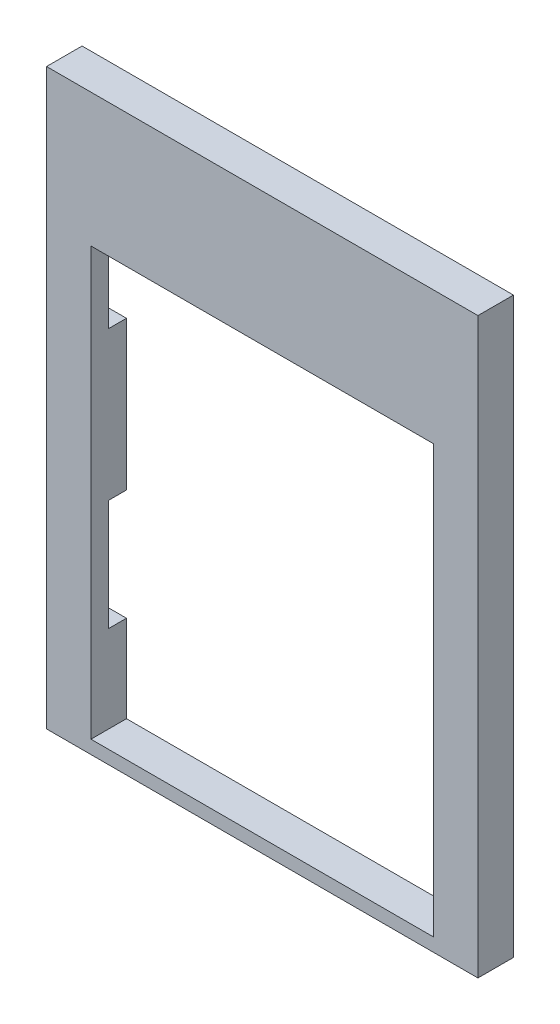
SolidWorks part; units mm, degrees
ref_plane "前视基准面" through (0, 0, 0) normal (0, 0, 1) x (1, 0, 0)
ref_plane "上视基准面" through (0, 0, 0) normal (0, 1, 0) x (1, 0, 0)
ref_plane "右视基准面" through (0, 0, 0) normal (1, 0, 0) x (0, 0, -1)
other "Configuration Table"
sketch "Model" plane through (0, 0, 0) normal (0, 0, 1) x (1, 0, 0)
  line L0 (114.6852, 14.7846) -> (114.6852, 10.0841)
  line L1 (114.6852, 10.0841) -> (113.1597, 10.0841)
  line L2 (113.1597, 10.0841) -> (113.1597, 13.3143)
  line L3 (113.1597, 13.3143) -> (106.4101, 13.3143)
  line L4 (106.4101, 13.3143) -> (106.4101, 10.0841)
  line L5 (106.4101, 10.0841) -> (105.5846, 10.0841)
  line L6 (105.5846, 10.0841) -> (105.5846, 7.2853)
  line L7 (105.5846, 7.2853) -> (106.4101, 7.2853)
  line L8 (106.4101, 7.2853) -> (106.4101, 1.0153)
  line L9 (106.4101, 1.0153) -> (108.1354, 1.0153)
  line L10 (108.1354, 1.0153) -> (108.1354, -0.185)
  line L11 (108.1354, -0.185) -> (111.4344, -0.185)
  line L12 (111.4344, -0.185) -> (111.4344, 1.0153)
  line L13 (111.4344, 1.0153) -> (113.1597, 1.0153)
  line L14 (113.1597, 1.0153) -> (113.1597, 5.4842)
  line L15 (113.1597, 5.4842) -> (114.6852, 5.4842)
  line L16 (114.6852, 5.4842) -> (114.6852, 0.7851)
  line L17 (114.6852, 0.7851) -> (128.6846, 0.7851)
  line L18 (128.6846, 0.7851) -> (128.6846, 5.4842)
  line L19 (128.6846, 5.4842) -> (130.2101, 5.4842)
  line L20 (130.2101, 5.4842) -> (130.2101, 1.0153)
  line L21 (130.2101, 1.0153) -> (131.9354, 1.0153)
  line L22 (131.9354, 1.0153) -> (131.9354, -0.185)
  line L23 (131.9354, -0.185) -> (135.2345, -0.185)
  line L24 (135.2345, -0.185) -> (135.2345, 1.0153)
  line L25 (135.2345, 1.0153) -> (136.9598, 1.0153)
  line L26 (136.9598, 1.0153) -> (136.9598, 7.2853)
  line L27 (136.9598, 7.2853) -> (137.7852, 7.2853)
  line L28 (137.7852, 7.2853) -> (137.7852, 10.0841)
  line L29 (137.7852, 10.0841) -> (136.9598, 10.0841)
  line L30 (136.9598, 10.0841) -> (136.9598, 13.3143)
  line L31 (136.9598, 13.3143) -> (130.2101, 13.3143)
  line L32 (130.2101, 13.3143) -> (130.2101, 10.0841)
  line L33 (130.2101, 10.0841) -> (128.6846, 10.0841)
  line L34 (128.6846, 10.0841) -> (128.6846, 14.7846)
  line L35 (128.6846, 14.7846) -> (114.6852, 14.7846)
  line L36 (143.2602, 14.7846) -> (157.2595, 14.7846)
  line L37 (157.2595, 14.7846) -> (157.2595, 0.7851)
  line L38 (157.2595, 0.7851) -> (143.2602, 0.7851)
  line L39 (143.2602, 0.7851) -> (143.2602, 14.7846)
  line L40 (168.8105, 33.4102) -> (168.8105, 32.5848)
  line L41 (168.8105, 32.5848) -> (162.5402, 32.5848)
  line L42 (162.5402, 32.5848) -> (162.5402, 30.8594)
  line L43 (162.5402, 30.8594) -> (161.3401, 30.8594)
  line L44 (161.3401, 30.8594) -> (161.3401, 27.5604)
  line L45 (161.3401, 27.5604) -> (162.5402, 27.5604)
  line L46 (162.5402, 27.5604) -> (162.5402, 25.8351)
  line L47 (162.5402, 25.8351) -> (167.0106, 25.8351)
  line L48 (167.0106, 25.8351) -> (167.0106, 24.3096)
  line L49 (167.0106, 24.3096) -> (162.3102, 24.3096)
  line L50 (162.3102, 24.3096) -> (162.3102, 10.3101)
  line L51 (162.3102, 10.3101) -> (167.0106, 10.3101)
  line L52 (167.0106, 10.3101) -> (167.0106, 8.7846)
  line L53 (167.0106, 8.7846) -> (162.5402, 8.7846)
  line L54 (162.5402, 8.7846) -> (162.5402, 7.0594)
  line L55 (162.5402, 7.0594) -> (161.3401, 7.0594)
  line L56 (161.3401, 7.0594) -> (161.3401, 3.7603)
  line L57 (161.3401, 3.7603) -> (162.5402, 3.7603)
  line L58 (162.5402, 3.7603) -> (162.5402, 2.035)
  line L59 (162.5402, 2.035) -> (168.8105, 2.035)
  line L60 (168.8105, 2.035) -> (168.8105, 1.2096)
  line L61 (168.8105, 1.2096) -> (171.6105, 1.2096)
  line L62 (171.6105, 1.2096) -> (171.6105, 2.035)
  line L63 (171.6105, 2.035) -> (174.8405, 2.035)
  line L64 (174.8405, 2.035) -> (174.8405, 8.7846)
  line L65 (174.8405, 8.7846) -> (171.6105, 8.7846)
  line L66 (171.6105, 8.7846) -> (171.6105, 10.3101)
  line L67 (171.6105, 10.3101) -> (176.3095, 10.3101)
  line L68 (176.3095, 10.3101) -> (176.3095, 24.3096)
  line L69 (176.3095, 24.3096) -> (171.6105, 24.3096)
  line L70 (171.6105, 24.3096) -> (171.6105, 25.8351)
  line L71 (171.6105, 25.8351) -> (174.8405, 25.8351)
  line L72 (174.8405, 25.8351) -> (174.8405, 32.5848)
  line L73 (174.8405, 32.5848) -> (171.6105, 32.5848)
  line L74 (171.6105, 32.5848) -> (171.6105, 33.4102)
  line L75 (171.6105, 33.4102) -> (168.8105, 33.4102)
  line L76 (105.1602, 33.8345) -> (119.1597, 33.8345)
  line L77 (119.1597, 33.8345) -> (119.1597, 19.8351)
  line L78 (119.1597, 19.8351) -> (105.1602, 19.8351)
  line L79 (105.1602, 19.8351) -> (105.1602, 33.8345)
  line L80 (124.2102, 33.8345) -> (138.2095, 33.8345)
  line L81 (138.2095, 33.8345) -> (138.2095, 19.8351)
  line L82 (138.2095, 19.8351) -> (124.2102, 19.8351)
  line L83 (124.2102, 19.8351) -> (124.2102, 33.8345)
  line L84 (143.2602, 33.8345) -> (157.2595, 33.8345)
  line L85 (157.2595, 33.8345) -> (157.2595, 19.8351)
  line L86 (157.2595, 19.8351) -> (143.2602, 19.8351)
  line L87 (143.2602, 19.8351) -> (143.2602, 33.8345)
  line L88 (105.1602, 52.8846) -> (119.1597, 52.8846)
  line L89 (119.1597, 52.8846) -> (119.1597, 38.8853)
  line L90 (119.1597, 38.8853) -> (105.1602, 38.8853)
  line L91 (105.1602, 38.8853) -> (105.1602, 52.8846)
  line L92 (124.2102, 52.8846) -> (138.2095, 52.8846)
  line L93 (138.2095, 52.8846) -> (138.2095, 38.8853)
  line L94 (138.2095, 38.8853) -> (124.2102, 38.8853)
  line L95 (124.2102, 38.8853) -> (124.2102, 52.8846)
  line L96 (143.2602, 52.8846) -> (157.2595, 52.8846)
  line L97 (157.2595, 52.8846) -> (157.2595, 38.8853)
  line L98 (157.2595, 38.8853) -> (143.2602, 38.8853)
  line L99 (143.2602, 38.8853) -> (143.2602, 52.8846)
  line L100 (168.8105, 71.5102) -> (168.8105, 70.6847)
  line L101 (168.8105, 70.6847) -> (162.5402, 70.6847)
  line L102 (162.5402, 70.6847) -> (162.5402, 68.9596)
  line L103 (162.5402, 68.9596) -> (161.3401, 68.9596)
  line L104 (161.3401, 68.9596) -> (161.3401, 65.6604)
  line L105 (161.3401, 65.6604) -> (162.5402, 65.6604)
  line L106 (162.5402, 65.6604) -> (162.5402, 63.935)
  line L107 (162.5402, 63.935) -> (167.0106, 63.935)
  line L108 (167.0106, 63.935) -> (167.0106, 62.4096)
  line L109 (167.0106, 62.4096) -> (162.3102, 62.4096)
  line L110 (162.3102, 62.4096) -> (162.3102, 48.4103)
  line L111 (162.3102, 48.4103) -> (167.0106, 48.4103)
  line L112 (167.0106, 48.4103) -> (167.0106, 46.8845)
  line L113 (167.0106, 46.8845) -> (162.5402, 46.8845)
  line L114 (162.5402, 46.8845) -> (162.5402, 45.1594)
  line L115 (162.5402, 45.1594) -> (161.3401, 45.1594)
  line L116 (161.3401, 45.1594) -> (161.3401, 41.8602)
  line L117 (161.3401, 41.8602) -> (162.5402, 41.8602)
  line L118 (162.5402, 41.8602) -> (162.5402, 40.1352)
  line L119 (162.5402, 40.1352) -> (168.8105, 40.1352)
  line L120 (168.8105, 40.1352) -> (168.8105, 39.3097)
  line L121 (168.8105, 39.3097) -> (171.6105, 39.3097)
  line L122 (171.6105, 39.3097) -> (171.6105, 40.1352)
  line L123 (171.6105, 40.1352) -> (174.8405, 40.1352)
  line L124 (174.8405, 40.1352) -> (174.8405, 46.8845)
  line L125 (174.8405, 46.8845) -> (171.6105, 46.8845)
  line L126 (171.6105, 46.8845) -> (171.6105, 48.4103)
  line L127 (171.6105, 48.4103) -> (176.3095, 48.4103)
  line L128 (176.3095, 48.4103) -> (176.3095, 62.4096)
  line L129 (176.3095, 62.4096) -> (171.6105, 62.4096)
  line L130 (171.6105, 62.4096) -> (171.6105, 63.935)
  line L131 (171.6105, 63.935) -> (174.8405, 63.935)
  line L132 (174.8405, 63.935) -> (174.8405, 70.6847)
  line L133 (174.8405, 70.6847) -> (171.6105, 70.6847)
  line L134 (171.6105, 70.6847) -> (171.6105, 71.5102)
  line L135 (171.6105, 71.5102) -> (168.8105, 71.5102)
  line L136 (105.1602, 71.9346) -> (119.1597, 71.9346)
  line L137 (119.1597, 71.9346) -> (119.1597, 57.9353)
  line L138 (119.1597, 57.9353) -> (105.1602, 57.9353)
  line L139 (105.1602, 57.9353) -> (105.1602, 71.9346)
  line L140 (124.2102, 71.9346) -> (138.2095, 71.9346)
  line L141 (138.2095, 71.9346) -> (138.2095, 57.9353)
  line L142 (138.2095, 57.9353) -> (124.2102, 57.9353)
  line L143 (124.2102, 57.9353) -> (124.2102, 71.9346)
  line L144 (143.2602, 71.9346) -> (157.2595, 71.9346)
  line L145 (157.2595, 71.9346) -> (157.2595, 57.9353)
  line L146 (157.2595, 57.9353) -> (143.2602, 57.9353)
  line L147 (143.2602, 57.9353) -> (143.2602, 71.9346)
  line L148 (105.1602, 90.9846) -> (119.1597, 90.9846)
  line L149 (119.1597, 90.9846) -> (119.1597, 76.9853)
  line L150 (119.1597, 76.9853) -> (105.1602, 76.9853)
  line L151 (105.1602, 76.9853) -> (105.1602, 90.9846)
  line L152 (124.2102, 90.9846) -> (138.2095, 90.9846)
  line L153 (138.2095, 90.9846) -> (138.2095, 76.9853)
  line L154 (138.2095, 76.9853) -> (124.2102, 76.9853)
  line L155 (124.2102, 76.9853) -> (124.2102, 90.9846)
  line L156 (143.2602, 90.9846) -> (157.2595, 90.9846)
  line L157 (157.2595, 90.9846) -> (157.2595, 76.9853)
  line L158 (157.2595, 76.9853) -> (143.2602, 76.9853)
  line L159 (143.2602, 76.9853) -> (143.2602, 90.9846)
  line L160 (162.3102, 90.9846) -> (176.3095, 90.9846)
  line L161 (176.3095, 90.9846) -> (176.3095, 76.9853)
  line L162 (176.3095, 76.9853) -> (162.3102, 76.9853)
  line L163 (162.3102, 76.9853) -> (162.3102, 90.9846)
  line L164 (102.1602, -2.2149) -> (102.1602, 23.8849)
  line L165 (179.3095, -2.2149) -> (179.3095, 23.8849)
  line L166 (179.3095, -2.2149) -> (102.1602, -2.2149)
  line L168 (96.1602, 79.3849) -> (96.1602, 97.3849)
  line L169 (98.1602, 97.3849) -> (98.1602, 94.3849)
  line L170 (98.1602, 79.3849) -> (98.1602, 82.3849)
  line L171 (92.1602, 118.9846) -> (92.1602, 123.9846)
  line L172 (102.1602, 35.8849) -> (102.1602, 82.3849)
  line L173 (179.3095, 35.8849) -> (179.3095, 82.3849)
  line L174 (179.3095, 35.8849) -> (179.3095, 82.3849)
  line L175 (92.1602, 123.9846) -> (189.3095, 123.9846)
  line L176 (185.3095, 79.3849) -> (185.3095, 97.3849)
  line L177 (183.3095, 97.3849) -> (183.3095, 94.3849)
  line L178 (183.3095, 79.3849) -> (183.3095, 82.3849)
  line L179 (96.1602, 38.8849) -> (96.1602, 20.8849)
  line L180 (98.1602, 20.8849) -> (98.1602, 23.8849)
  line L181 (98.1602, 38.8849) -> (98.1602, 35.8849)
  line L182 (185.3095, 38.8849) -> (185.3095, 20.8849)
  line L183 (183.3095, 20.8849) -> (183.3095, 23.8849)
  line L184 (183.3095, 38.8849) -> (183.3095, 35.8849)
  line L185 (102.1602, 35.8849) -> (102.1602, 23.8849)
  line L186 (112.16, 93.9846) -> (135.2345, 93.9846)
  line L187 (102.1602, 94.3849) -> (102.1602, 82.3849)
  line L188 (179.3095, 94.3849) -> (179.3095, 82.3849)
  line L189 (135.2345, 93.9846) -> (179.3095, 93.9846)
  line L190 (112.16, 93.9846) -> (102.1602, 93.9846)
  line L191 (179.3095, 35.8849) -> (179.3095, 23.8849)
  line L194 (102.1602, -2.2149) -> (102.1602, -5.2149)
  line L195 (102.1602, -5.2149) -> (93.1602, -5.2149)
  line L196 (93.1602, -5.2149) -> (188.3095, -5.2149)
  line L197 (189.3095, 123.9846) -> (189.3095, 118.9846)
  line L198 (92.1602, 118.9846) -> (92.1602, -5.2149)
  line L199 (189.3095, 118.9846) -> (189.3095, -5.2149)
  line L201 (189.3095, -5.2149) -> (92.1602, -5.2149)
  arc A0 (97.1602, 98.3849) -> (96.1602, 97.3849) centre (97.1602, 97.3849) ccw
  arc A1 (98.1602, 97.3849) -> (97.1602, 98.3849) centre (97.1602, 97.3849) ccw
  arc A2 (96.1602, 79.3849) -> (97.1602, 78.3849) centre (97.1602, 79.3849) ccw
  arc A3 (97.1602, 78.3849) -> (98.1602, 79.3849) centre (97.1602, 79.3849) ccw
  arc A4 (98.1602, 94.3849) -> (100.1602, 92.3849) centre (100.1602, 94.3849) ccw
  arc A5 (100.1602, 92.3849) -> (102.1602, 94.3849) centre (100.1602, 94.3849) ccw
  arc A6 (100.1602, 84.3849) -> (98.1602, 82.3849) centre (100.1602, 82.3849) ccw
  arc A7 (102.1602, 82.3849) -> (100.1602, 84.3849) centre (100.1602, 82.3849) ccw
  arc A8 (181.3095, 84.3849) -> (179.3095, 82.3849) centre (181.3095, 82.3849) ccw
  arc A9 (179.3095, 94.3849) -> (181.3095, 92.3849) centre (181.3095, 94.3849) ccw
  arc A10 (185.3095, 97.3849) -> (184.3095, 98.3849) centre (184.3095, 97.3849) ccw
  arc A11 (184.3095, 98.3849) -> (183.3095, 97.3849) centre (184.3095, 97.3849) ccw
  arc A12 (183.3095, 82.3849) -> (181.3095, 84.3849) centre (181.3095, 82.3849) ccw
  arc A13 (183.3095, 79.3849) -> (184.3095, 78.3849) centre (184.3095, 79.3849) ccw
  arc A14 (184.3095, 78.3849) -> (185.3095, 79.3849) centre (184.3095, 79.3849) ccw
  arc A15 (181.3095, 92.3849) -> (183.3095, 94.3849) centre (181.3095, 94.3849) ccw
  arc A16 (100.1602, 33.8849) -> (102.1602, 35.8849) centre (100.1602, 35.8849) ccw
  arc A17 (102.1602, 23.8849) -> (100.1602, 25.8849) centre (100.1602, 23.8849) ccw
  arc A18 (96.1602, 20.8849) -> (97.1602, 19.8849) centre (97.1602, 20.8849) ccw
  arc A19 (97.1602, 19.8849) -> (98.1602, 20.8849) centre (97.1602, 20.8849) ccw
  arc A20 (98.1602, 35.8849) -> (100.1602, 33.8849) centre (100.1602, 35.8849) ccw
  arc A21 (98.1602, 38.8849) -> (97.1602, 39.8849) centre (97.1602, 38.8849) ccw
  arc A22 (97.1602, 39.8849) -> (96.1602, 38.8849) centre (97.1602, 38.8849) ccw
  arc A23 (100.1602, 25.8849) -> (98.1602, 23.8849) centre (100.1602, 23.8849) ccw
  arc A24 (179.3095, 35.8849) -> (181.3095, 33.8849) centre (181.3095, 35.8849) ccw
  arc A25 (181.3095, 25.8849) -> (179.3095, 23.8849) centre (181.3095, 23.8849) ccw
  arc A26 (184.3095, 19.8849) -> (185.3095, 20.8849) centre (184.3095, 20.8849) ccw
  arc A27 (183.3095, 20.8849) -> (184.3095, 19.8849) centre (184.3095, 20.8849) ccw
  arc A28 (181.3095, 33.8849) -> (183.3095, 35.8849) centre (181.3095, 35.8849) ccw
  arc A29 (184.3095, 39.8849) -> (183.3095, 38.8849) centre (184.3095, 38.8849) ccw
  arc A30 (185.3095, 38.8849) -> (184.3095, 39.8849) centre (184.3095, 38.8849) ccw
  arc A31 (183.3095, 23.8849) -> (181.3095, 25.8849) centre (181.3095, 23.8849) ccw
extrude "凸台-拉伸1" add sketch "Model" along normal mid plane 8
sketch "草图4" plane through (0, 0, 0) normal (0, 0, 1) x (1, 0, 0)
  line L164 (102.1602, 42.3849) -> (102.1602, 17.3849)
  line L186 (179.3095, 100.8849) -> (179.3095, 75.8849)
  line L187 (179.3095, 75.8849) -> (187.3095, 75.8849)
  line L188 (102.1602, 100.8849) -> (102.1602, 75.8849)
  line L189 (102.1602, 100.8849) -> (94.1602, 100.8849)
  line L190 (102.1602, 75.8849) -> (94.1602, 75.8849)
  line L191 (94.1602, 100.8849) -> (94.1602, 75.8849)
  line L192 (187.3095, 100.8849) -> (187.3095, 75.8849)
  line L193 (179.3095, 100.8849) -> (187.3095, 100.8849)
  line L194 (179.3095, 42.3849) -> (179.3095, 17.3849)
  line L195 (179.3095, 42.3849) -> (187.3095, 42.3849)
  line L196 (187.3095, 42.3849) -> (187.3095, 17.3849)
  line L198 (102.1602, 42.3849) -> (94.1602, 42.3849)
  line L199 (102.1602, 17.3849) -> (94.1602, 17.3849)
  line L200 (94.1602, 42.3849) -> (94.1602, 17.3849)
  line L201 (179.3095, 17.3849) -> (187.3095, 17.3849)
extrude "切除-拉伸1" cut sketch "草图4" against normal through all
